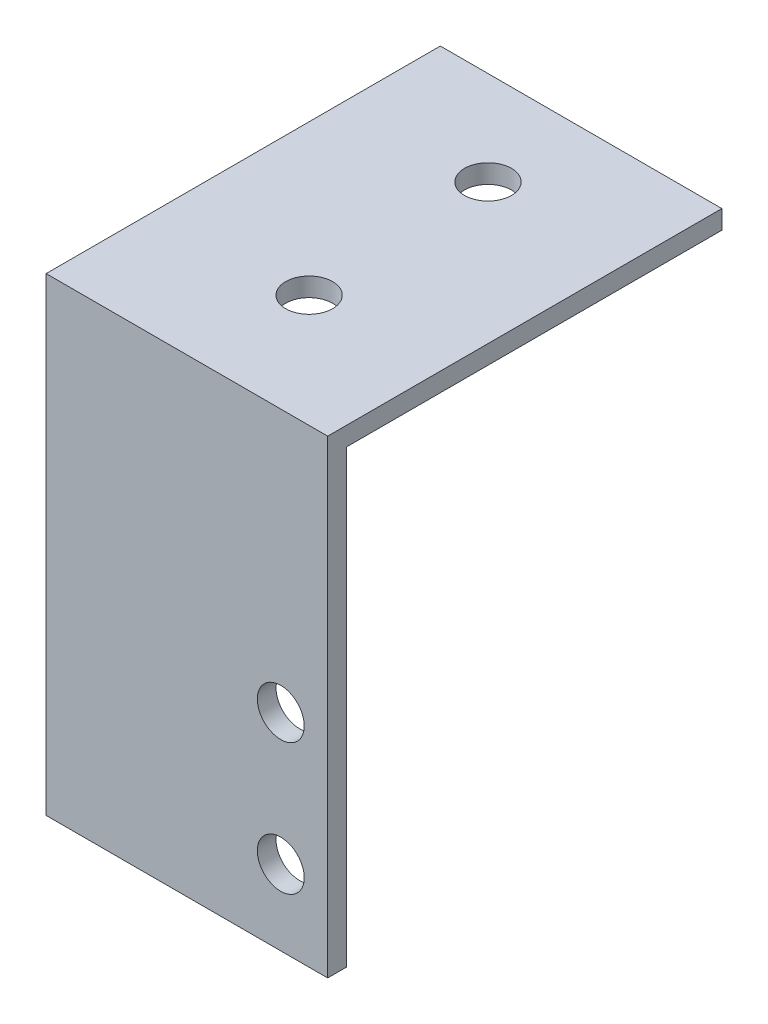
SolidWorks part; units mm, degrees
ref_plane "正面" through (0, 0, 0) normal (0, 0, 1) x (1, 0, 0)
ref_plane "平面" through (0, 0, 0) normal (0, 1, 0) x (1, 0, 0)
ref_plane "右側面" through (0, 0, 0) normal (1, 0, 0) x (0, 0, -1)
sketch "ｽｹｯﾁ1" plane through (0, 0, 0) normal (0, 0, 1) x (1, 0, 0)
  line L1 (0, 0) -> (15, 0)
  line L2 (0, 0) -> (0, 25)
  line L3 (0, 25) -> (15, 25)
  line L4 (15, 0) -> (15, 25)
  dimension "D1" = 25
  dimension "D2" = 15
extrude "ﾎﾞｽ - 押し出し1" add sketch "ｽｹｯﾁ1" along normal blind 1 contours L3 L4 L1 L2
hole_wizard "M3x0.5 ねじ穴1" positions "ｽｹｯﾁ2" profile "ｽｹｯﾁ3" tap size "M3x0.5" standard "JIS"
sketch "ｽｹｯﾁ2" plane through (0, 0, 0) normal (0, 0, -1) x (-1, 0, 0)
  line L2 (-15, 0) -> (-15, 25) construction
  line L3 (0, 0) -> (-15, 0) construction
  point P0 (-12.5, 11)
  point P2 (-12.5, 4)
  dimension "D1" = 2.5
  dimension "D2" = 2.5
  dimension "D3" = 4
  dimension "D4" = 7
sketch "ｽｹｯﾁ3" plane through (12.5, 11, 0) normal (1, 0, 0) x (0, 1, 0)
  line L0 (0, 0) -> (0, 9.2511)
  line L1 (0, 9.2511) -> (1.25, 8.5)
  line L2 (1.25, 8.5) -> (1.25, 0)
  line L5 (1.25, 0) -> (0, 0)
  line L10 (0, 9.2511) -> (-1.25, 8.5) construction
  line L11 (0, -6.35) -> (0, 107.95) construction
  dimension "ねじ下穴ﾄﾞﾘﾙ直径" = 2.5
  dimension "ねじ下穴ﾄﾞﾘﾙの深さ" = 8.5
  dimension "ﾄﾞﾘﾙ角度" = 118
sketch "ｽｹｯﾁ4" plane through (0, 0, 0) normal (0, 0, -1) x (-1, 0, 0)
  line L0 (-15, 0) -> (-15, 25) construction
  line L1 (0, 25) -> (-15, 25)
  line L2 (0, 25) -> (0, 24)
  line L3 (0, 24) -> (-15, 24)
  line L4 (-15, 25) -> (-15, 24)
  dimension "D1" = 1
extrude "ﾎﾞｽ - 押し出し2" add sketch "ｽｹｯﾁ4" along normal blind 20
ref_plane "平面1" through (5, 0, 0) normal (1, 0, 0) x (0, 0, -1)
hole_wizard "M3x0.5 ねじ穴2" positions "ｽｹｯﾁ5" profile "ｽｹｯﾁ6" tap size "M3x0.5" standard "JIS"
sketch "ｽｹｯﾁ5" plane through (0, 24, 0) normal (0, -1, 0) x (-1, 0, 0)
  line L0 (-15, 20) -> (0, 20) construction
  line L1 (-15, 20) -> (-15, 0) construction
  point P0 (-8, 5.0106)
  point P2 (-7.54, 15)
  dimension "D1" = 5
  dimension "D2" = 10
  dimension "D3" = 7
sketch "ｽｹｯﾁ6" plane through (8, 24, -5.0106) normal (1, 0, 0) x (0, 0, -1)
  line L0 (0, 0) -> (0, 9.2511)
  line L1 (0, 9.2511) -> (1.25, 8.5)
  line L2 (1.25, 8.5) -> (1.25, 0)
  line L5 (1.25, 0) -> (0, 0)
  line L10 (0, 9.2511) -> (-1.25, 8.5) construction
  line L11 (0, -6.35) -> (0, 107.95) construction
  dimension "ねじ下穴ﾄﾞﾘﾙ直径" = 2.5
  dimension "ねじ下穴ﾄﾞﾘﾙの深さ" = 8.5
  dimension "ﾄﾞﾘﾙ角度" = 118
